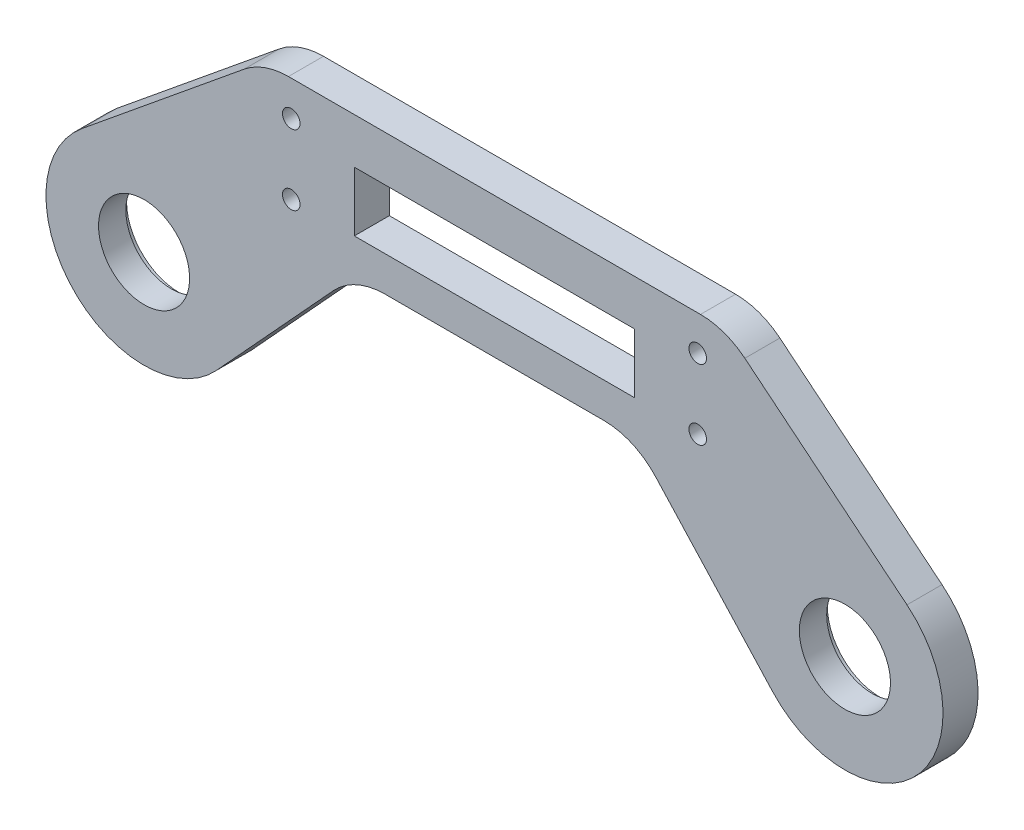
SolidWorks part; units mm, degrees
ref_plane "前视基准面" through (0, 0, 0) normal (0, 0, 1) x (1, 0, 0)
ref_plane "上视基准面" through (0, 0, 0) normal (0, 1, 0) x (1, 0, 0)
ref_plane "右视基准面" through (0, 0, 0) normal (1, 0, 0) x (0, 0, -1)
sketch "草图3" plane through (0, 0, 0) normal (0, 0, 1) x (1, 0, 0)
  line L0 (-35.7232, 7.7438) -> (-58.858, -11.1586)
  line L1 (-15.6022, -10) -> (15.6022, -10)
  line L3 (-29.3961, 10) -> (29.3961, 10)
  line L5 (-32.9619, -10) -> (32.9619, 10) construction
  line L6 (-32.9619, 10) -> (27.0109, -8.1946) construction
  line L7 (35.7232, 7.7438) -> (58.858, -11.1586)
  line L8 (-22.9724, -13.2413) -> (-39.6818, -31.4622)
  line L9 (22.9724, -13.2413) -> (39.6818, -31.4622)
  arc A0 (39.6818, -31.4622) -> (58.858, -11.1586) centre (50, -22) ccw
  arc A1 (-58.858, -11.1586) -> (-39.6818, -31.4622) centre (-50, -22) ccw
  arc A2 (15.6022, -10) -> (22.9724, -13.2413) centre (15.6022, -20) cw
  arc A3 (-15.6022, -10) -> (-22.9724, -13.2413) centre (-15.6022, -20) ccw
  arc A4 (35.7232, 7.7438) -> (29.3961, 10) centre (29.3961, 0) ccw
  arc A5 (-29.3961, 10) -> (-35.7232, 7.7438) centre (-29.3961, 0) ccw
  point P0 (0, 0)
  point P8 (0, 10)
  dimension "D1" = 100
  dimension "D8" = 28
  dimension "D9" = 28
  dimension "D3" = 10
  dimension "D2" = 50
  dimension "D4" = 0
  dimension "D5" = 60
  dimension "D6" = 20
extrude "凸台-拉伸1" add sketch "草图3" along normal blind 5
sketch "草图4" plane through (0, 0, 5) normal (0, 0, 1) x (1, 0, 0)
  line L0 (-15.6022, -10) -> (15.6022, -10) construction
  line L1 (-20, -5) -> (20, -5)
  line L2 (-20, -5) -> (-20, 3.5)
  line L3 (-20, 3.5) -> (20, 3.5)
  line L4 (20, -5) -> (20, 3.5)
  point P7 (0, -5)
  dimension "D1" = 40
  dimension "D2" = 8.5
  dimension "D3" = 5
  dimension "D4" = 0
extrude "切除-拉伸1" cut sketch "草图4" against normal blind 5
sketch "草图5" plane through (0, 0, 5) normal (0, 0, 1) x (1, 0, 0)
  line L0 (-20, -5) -> (20, -5) construction
  line L1 (-15.6022, -10) -> (15.6022, -10) construction
  circle A0 centre (-29, -5) radius 1.25
  circle A1 centre (-29, 5) radius 1.25
  point P6 (0, -5)
  dimension "D1" = 2.5
  dimension "D2" = 2.5
  dimension "D3" = 29
  dimension "D4" = 29
  dimension "D5" = 5
  dimension "D6" = 10
extrude "切除-拉伸2" cut sketch "草图5" against normal blind 7
sketch "草图9" plane through (0, 0, 0) normal (0, 0, -1) x (-1, 0, 0)
  circle A0 centre (-50, -22) radius 6.5
  circle A1 centre (50, -22) radius 6.5
extrude "切除-拉伸4" cut sketch "草图9" against normal blind 5
sketch "草图10" plane through (0, 0, 0) normal (0, 0, -1) x (-1, 0, 0)
  circle A0 centre (-50, -22) radius 7.5
  circle A1 centre (50, -22) radius 7.5
extrude "切除-拉伸5" cut sketch "草图10" against normal blind 1.1
ref_plane "基准面3" through (0, 0, 0) normal (-1, 0, 0) x (0, 0, 1)
mirror "镜向1" about plane through (0, 0, 0) normal (-1, 0, 0) of "切除-拉伸2"
